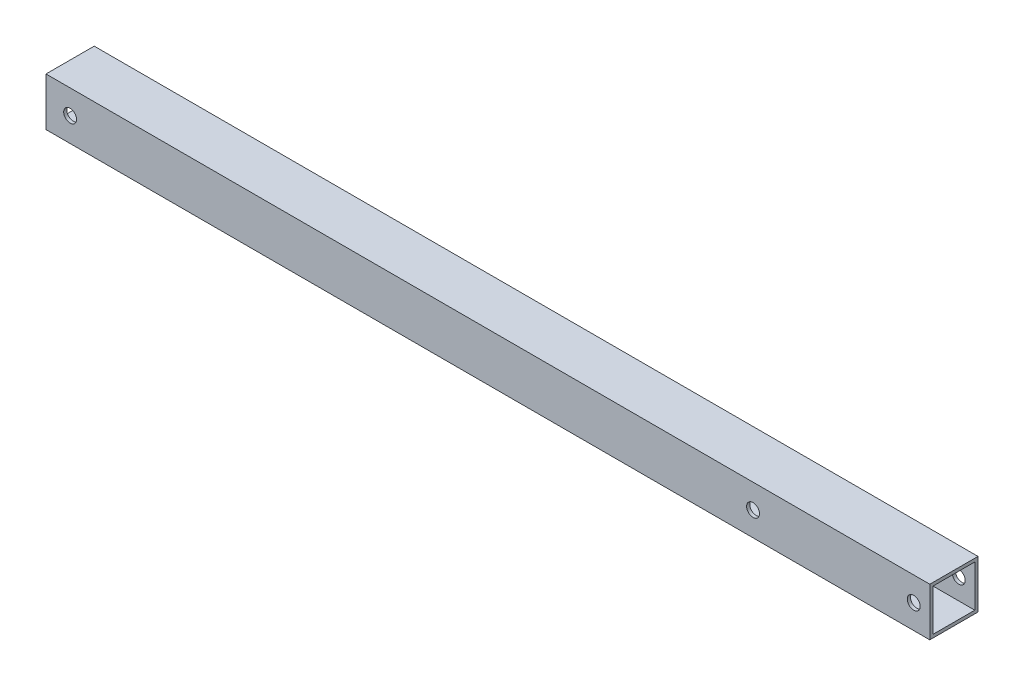
SolidWorks part; units mm, degrees
ref_plane "Front Plane" through (0, 0, 0) normal (0, 0, 1) x (1, 0, 0)
ref_plane "Top Plane" through (0, 0, 0) normal (0, 1, 0) x (1, 0, 0)
ref_plane "Right Plane" through (0, 0, 0) normal (1, 0, 0) x (0, 0, -1)
sketch "Sketch1" plane through (0, 0, 0) normal (1, 0, 0) x (0, 0, -1)
  line L1 (0, 0) -> (30, 0)
  line L2 (0, 0) -> (0, 30)
  line L3 (0, 30) -> (30, 30)
  line L4 (30, 0) -> (30, 30)
  line L5 (2, 2) -> (28, 2)
  line L6 (2, 2) -> (2, 28)
  line L7 (2, 28) -> (28, 28)
  line L8 (28, 2) -> (28, 28)
  dimension "D1" = 30
  dimension "D2" = 30
  dimension "D3" = 2
  dimension "D4" = 2
  dimension "D5" = 2
  dimension "D6" = 2
extrude "Boss-Extrude1" add sketch "Sketch1" along normal blind 550
sketch "Sketch2" plane through (0, 0, 0) normal (0, 0, 1) x (1, 0, 0)
  line L0 (550, 30) -> (550, 0) construction
  line L1 (550, 0) -> (0, 0) construction
  line L2 (550, 30) -> (0, 30) construction
  line L3 (0, 30) -> (0, 0) construction
  circle A0 centre (15, 15) radius 4
  circle A2 centre (440, 15) radius 4
  circle A3 centre (540, 15) radius 4
  dimension "D1" = 8
  dimension "D4" = 8
  dimension "D9" = 8
  dimension "D2" = 110
  dimension "D3" = 15
  dimension "D5" = 15
  dimension "D6" = 100
  dimension "D7" = 15
  dimension "D8" = 15
extrude "Cut-Extrude1" cut sketch "Sketch2" against normal through all both and the other way through all
